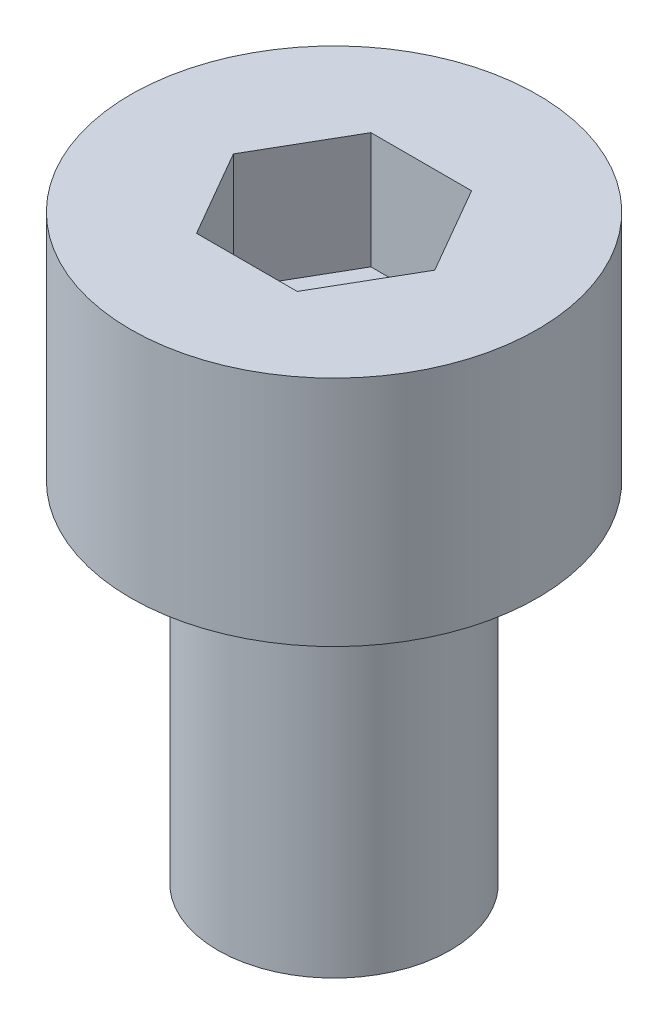
SolidWorks part; units mm, degrees
material "AISI 304"
ref_plane "Front Plane" through (0, 0, 0) normal (0, 0, 1) x (1, 0, 0)
ref_plane "Top Plane" through (0, 0, 0) normal (0, 1, 0) x (1, 0, 0)
ref_plane "Right Plane" through (0, 0, 0) normal (1, 0, 0) x (0, 0, -1)
sketch "Sketch1" plane through (0, 0, 0) normal (0, 0, 1) x (1, 0, 0)
  line L0 (0, 61.6916) -> (0, -59.3578) construction
  line L1 (0, -6) -> (2, -6)
  line L2 (2, -6) -> (2, 0)
  line L3 (2, 0) -> (3.5, 0)
  line L4 (3.5, 0) -> (3.5, 4)
  line L5 (3.5, 4) -> (0, 4)
  line L6 (0, 4) -> (0, -6)
  dimension "D1" = 6
  dimension "D2" = 7
  dimension "D3" = 4
  dimension "D4" = 4
revolve "Revolve1" add sketch "Sketch1" angle 360 about L0
sketch "Sketch2" plane through (0, 4, 0) normal (0, 1, 0) x (-1, 0, 0)
  line L1 (-0.866, -1.5) -> (0.866, -1.5)
  line L2 (0.866, -1.5) -> (1.7321, 0)
  line L3 (1.7321, 0) -> (0.866, 1.5)
  line L4 (0.866, 1.5) -> (-0.866, 1.5)
  line L5 (-0.866, 1.5) -> (-1.7321, 0)
  line L6 (-1.7321, 0) -> (-0.866, -1.5)
  circle A0 centre (0, 0) radius 1.5 construction
  dimension "D1" = 3
extrude "Cut-Extrude1" cut sketch "Sketch2" against normal blind 2
